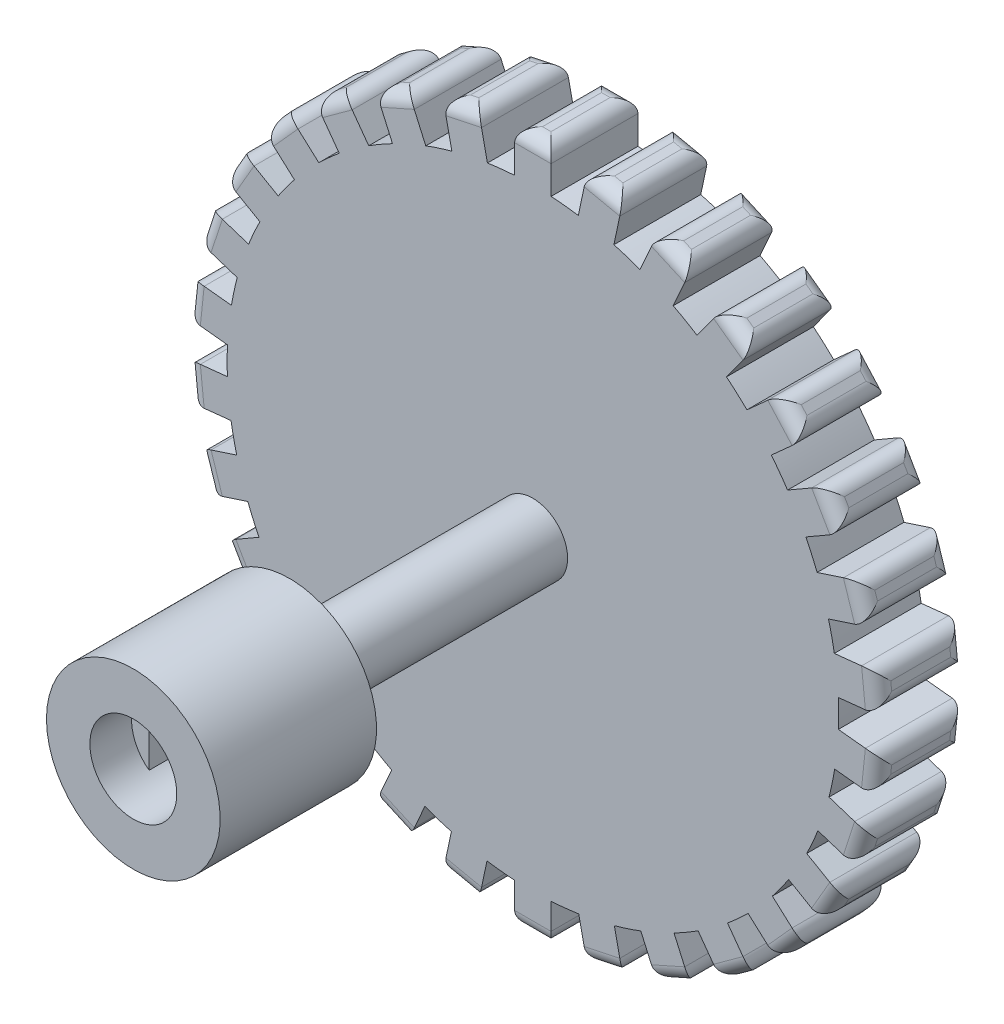
SolidWorks part; units mm, degrees
ref_plane "Front Plane" through (0, 0, 0) normal (0, 0, 1) x (1, 0, 0)
ref_plane "Top Plane" through (0, 0, 0) normal (0, 1, 0) x (1, 0, 0)
ref_plane "Right Plane" through (0, 0, 0) normal (1, 0, 0) x (0, 0, -1)
sketch "Sketch1" plane through (0, 0, 0) normal (0, 0, 1) x (1, 0, 0)
  circle A0 centre (0, 0) radius 88
extrude "Boss-Extrude3" add sketch "Sketch1" along normal blind 25
sketch "Sketch4" plane through (0, 0, 25) normal (0, 0, 1) x (1, 0, 0)
  line L0 (0, 88) -> (0, 100) construction
  line L1 (5.236, 100) -> (-5.236, 100)
  line L2 (-5.236, 100) -> (-5.236, 86.6488)
  line L3 (-5.236, 86.6488) -> (5.236, 86.6488)
  line L4 (5.236, 86.6488) -> (5.236, 100)
  circle A0 centre (0, 0) radius 88 construction
  point P9 (0, 100)
extrude "Boss-Extrude4" add sketch "Sketch4" against normal blind 25
fillet "Fillet2" radius 4 4 edges at (-5.236, 100, 12.5) (0, 100, 0) (5.236, 100, 12.5) (0, 100, 25)
pattern_circular "CirPattern1" count 30 over 360 about axis through (0, 0.3177, 0) along (0, 0, 1) of "Fillet2", "Boss-Extrude4"
ref_plane "Plane1" through (-5.236, 96, 25) normal (-1, 0, 0) x (0, 0, 1)
sketch "Sketch6" plane through (0, 0, 25) normal (0, 0, 1) x (1, 0, 0)
  circle A0 centre (0, 0) radius 10
extrude "Boss-Extrude5" add sketch "Sketch6" along normal blind 60
sketch "Sketch7" plane through (0, 0, 0) normal (0, 0, -1) x (-1, 0, 0)
  circle A0 centre (0, 0) radius 10
extrude "Boss-Extrude6" add sketch "Sketch7" along normal blind 10
sketch "Sketch8" plane through (0, 0, 85) normal (0, 0, 1) x (1, 0, 0)
  circle A0 centre (0, 0) radius 10
extrude "Boss-Extrude7" add sketch "Sketch8" along normal blind 10
sketch "Sketch9" plane through (0, 0, 95) normal (0, 0, 1) x (1, 0, 0)
  circle A0 centre (0, 0) radius 10
extrude "Boss-Extrude8" add sketch "Sketch9" along normal blind 25
sketch "Sketch10" plane through (0, 0, 120) normal (0, 0, 1) x (1, 0, 0)
  circle A0 centre (0, 0) radius 10
extrude "Boss-Extrude9" add sketch "Sketch10" along normal blind 42.5
sketch "Sketch12" plane through (0, 0, 162.5) normal (0, 0, 1) x (1, 0, 0)
  circle A0 centre (0, 0) radius 12.5
extrude "Cut-Extrude1" cut sketch "Sketch12" against normal blind 12
sketch "Sketch13" plane through (0, 0, 150.5) normal (0, 0, 1) x (1, 0, 0)
  circle A0 centre (0, 0) radius 10
extrude "Cut-Extrude2" cut sketch "Sketch13" against normal blind 55.5
sketch "Sketch14" plane through (0, 0, 95) normal (0, 0, 1) x (1, 0, 0)
  circle A0 centre (0, 0) radius 25
extrude "Boss-Extrude10" add sketch "Sketch14" along normal blind 45
sketch "Sketch15" plane through (0, 0, 140) normal (0, 0, 1) x (1, 0, 0)
  circle A0 centre (0, 0) radius 12.5
extrude "Cut-Extrude3" cut sketch "Sketch15" against normal blind 12
sketch "Sketch16" plane through (0, 0, 128) normal (0, 0, 1) x (1, 0, 0)
  line L2 (7.45, -10.0373) -> (7.45, 10.0373)
  line L4 (-7.45, -10.0373) -> (-7.45, 10.0373)
  line L5 (3.5287, -11.9916) -> (-3.5287, 11.9916) construction
  line L6 (3.5287, 11.9916) -> (-3.5287, -11.9916) construction
  arc A0 (7.45, 10.0373) -> (-7.45, 10.0373) centre (0, 0) ccw
  arc A1 (-7.45, -10.0373) -> (7.45, -10.0373) centre (0, 0) ccw
  point P0 (0, 0)
extrude "Cut-Extrude4" cut sketch "Sketch16" against normal blind 30.5
scale "Scale1" bodies to scale 122 scale about centroid uniform scaling yes scale factor 0.2
